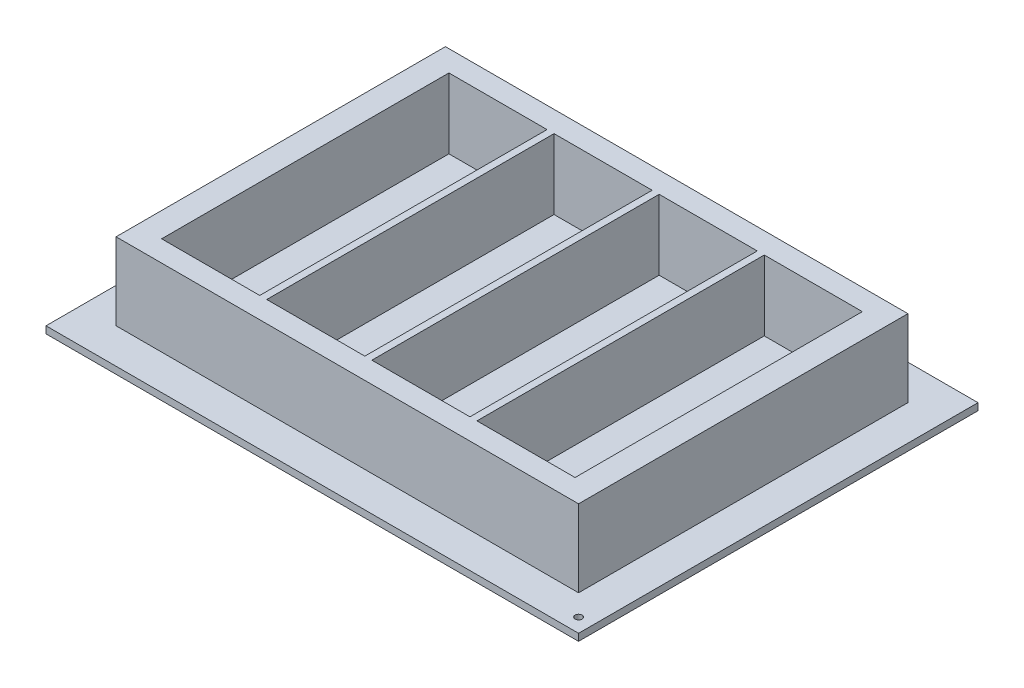
SolidWorks part; units mm, degrees
ref_plane "Front Plane" through (0, 0, 0) normal (0, 0, 1) x (1, 0, 0)
ref_plane "Top Plane" through (0, 0, 0) normal (0, 1, 0) x (1, 0, 0)
ref_plane "Right Plane" through (0, 0, 0) normal (1, 0, 0) x (0, 0, -1)
sketch "Sketch1" plane through (0, 0, 0) normal (0, 1, 0) x (1, 0, 0)
  line L1 (-29.5, 20.5) -> (29.5, 20.5)
  line L2 (-29.5, 20.5) -> (-29.5, -20.5)
  line L3 (-29.5, -20.5) -> (29.5, -20.5)
  line L4 (29.5, 20.5) -> (29.5, -20.5)
  line L5 (-29.5, 20.5) -> (29.5, -20.5) construction
  line L6 (-29.5, -20.5) -> (29.5, 20.5) construction
  line L7 (-33, 23.5) -> (33, 23.5)
  line L8 (-33, 23.5) -> (-33, -23.5)
  line L9 (-33, -23.5) -> (33, -23.5)
  line L10 (33, 23.5) -> (33, -23.5)
  line L11 (-33, 23.5) -> (33, -23.5) construction
  line L12 (-33, -23.5) -> (33, 23.5) construction
  point P0 (0, 0)
  point P6 (0, 0)
  dimension "D1" = 59
  dimension "D2" = 41
  dimension "D3" = 47
  dimension "D4" = 66
extrude "Boss-Extrude1" add sketch "Sketch1" along normal blind 10
sketch "Sketch3" plane through (0, 0, 0) normal (0, -1, 0) x (-1, 0, 0)
  line L1 (33, -23.5) -> (-33, -23.5)
  line L2 (33, -23.5) -> (33, 23.5)
  line L3 (33, 23.5) -> (-33, 23.5)
  line L4 (-33, -23.5) -> (-33, 23.5)
  line L5 (33, -23.5) -> (-33, 23.5) construction
  line L6 (33, 23.5) -> (-33, -23.5) construction
  point P0 (0, 0)
extrude "Boss-Extrude2" add sketch "Sketch3" along normal blind 1
sketch "Sketch6" plane through (0, 10, 0) normal (0, 1, 0) x (1, 0, 0)
  line L1 (0, 27.7024) -> (0, -25.9243)
  line L9 (-15.5, 20.5) -> (-14.5, 20.5)
  line L10 (-15.5, 20.5) -> (-15.5, -20.5)
  line L11 (-15.5, -20.5) -> (-14.5, -20.5)
  line L12 (-14.5, 20.5) -> (-14.5, -20.5)
  line L13 (-15.5, 20.5) -> (-14.5, -20.5) construction
  line L14 (-15.5, -20.5) -> (-14.5, 20.5) construction
  line L19 (-0.5, 20.5) -> (0.5, 20.5)
  line L20 (-0.5, 20.5) -> (-0.5, -20.5)
  line L21 (14.5, 20.5) -> (15.5, 20.5)
  line L22 (14.5, 20.5) -> (14.5, -20.5)
  line L23 (14.5, -20.5) -> (15.5, -20.5)
  line L24 (15.5, 20.5) -> (15.5, -20.5)
  line L25 (14.5, 20.5) -> (15.5, -20.5) construction
  line L26 (14.5, -20.5) -> (15.5, 20.5) construction
  line L27 (-0.5, -20.5) -> (0.5, -20.5)
  line L28 (0.5, 20.5) -> (0.5, -20.5)
  line L29 (-0.5, 20.5) -> (0.5, -20.5) construction
  line L30 (-0.5, -20.5) -> (0.5, 20.5) construction
  point P16 (-15, 0)
  point P17 (0, 0)
  point P19 (15, 0)
  point P20 (-15, 0)
  point P25 (0, 0)
  point P30 (15, 0)
  line M7 (-29.5, 20.5) -> (29.5, 20.5)
  line M9 (29.5, -20.5) -> (-29.5, -20.5)
  dimension "D4" = 1
  dimension "D5" = 1
  dimension "D6" = 41
  dimension "D7" = 1
extrude "Boss-Extrude3" add sketch "Sketch6" against normal blind 10 contours L12 L10 M7 M9 | L20 L1 M7 M9 | L28 L1 M7 M9 | L24 L22 M7 M9
sketch "Sketch7" plane through (0, -1, 0) normal (0, -1, 0) x (-1, 0, 0)
  line L1 (38, -28.5) -> (-38, -28.5)
  line L2 (38, -28.5) -> (38, 28.5)
  line L3 (38, 28.5) -> (-38, 28.5)
  line L4 (-38, -28.5) -> (-38, 28.5)
  line L5 (38, -28.5) -> (-38, 28.5) construction
  line L6 (38, 28.5) -> (-38, -28.5) construction
  point P0 (0, 0)
  dimension "D1" = 57
  dimension "D2" = 76
extrude "Boss-Extrude4" add sketch "Sketch7" along normal blind 1
sketch "Sketch8" plane through (0, -1, 0) normal (0, 1, 0) x (1, 0, 0)
  line L0 (-38, -28.5) -> (-38, 28.5) construction
  line L1 (-38, 28.5) -> (38, 28.5) construction
  line L2 (38, 28.5) -> (38, -28.5) construction
  line L3 (38, -28.5) -> (-38, -28.5) construction
  circle A0 centre (-36, 26.5) radius 0.5
  circle A1 centre (36, -26.5) radius 0.5
  dimension "D1" = 1
  dimension "D2" = 1
  dimension "D3" = 2
  dimension "D4" = 2
  dimension "D5" = 2
  dimension "D6" = 2
extrude "Cut-Extrude1" cut sketch "Sketch8" against normal blind 1
